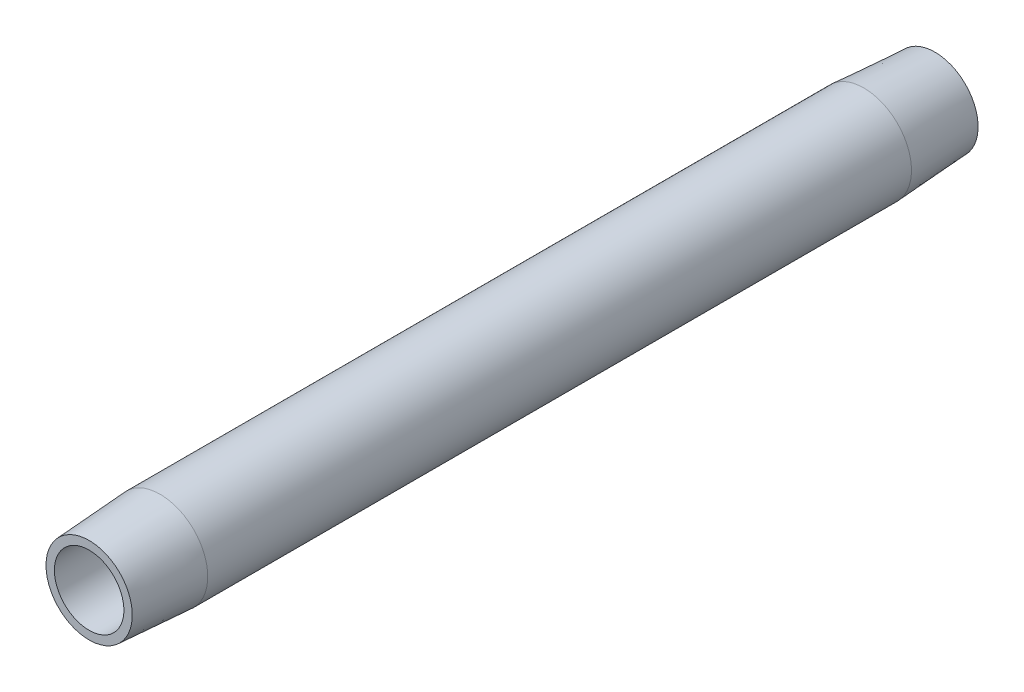
SolidWorks part; units mm, degrees
material "Low Carbon Steel"
ref_plane "Front Plane" through (0, 0, 0) normal (0, 0, 1) x (1, 0, 0)
ref_plane "Top Plane" through (0, 0, 0) normal (0, 1, 0) x (1, 0, 0)
ref_plane "Right Plane" through (0, 0, 0) normal (1, 0, 0) x (0, 0, -1)
ref_plane "Plane1" through (0, 0, 0) normal (0, -1, 0) x (1, 0, 0)
sketch "Sketch1" plane through (0, 0, 0) normal (0, -1, 0) x (1, 0, 0)
  line L0 (8.5725, -139.6004) -> (8.5725, -12.7996)
  line L1 (8.5725, -12.7996) -> (7.7725, 0)
  line L2 (7.7725, 0) -> (6.2611, 0)
  line L3 (6.2611, 0) -> (6.2611, -152.4)
  line L4 (6.2611, -152.4) -> (7.7725, -152.4)
  line L5 (7.7725, -152.4) -> (8.5725, -139.6004)
  line L6 (0, 0) -> (0, -88.9) construction
  point P10 (7.0168, 0)
  dimension "D1" = 12.5222
  dimension "D2" = 17.145
  dimension "D3" = 12.7996
  dimension "D4" = 15.5451
  dimension "D5" = 152.4
revolve "Revolve1" add sketch "Sketch1" angle 360 about L6
